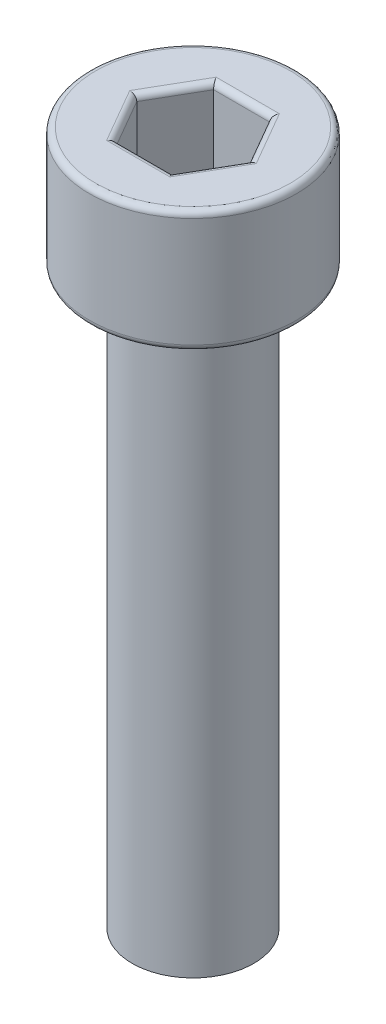
SolidWorks part; units mm, degrees
ref_plane "Front Plane" through (0, 0, 0) normal (0, 0, 1) x (1, 0, 0)
ref_plane "Top Plane" through (0, 0, 0) normal (0, 1, 0) x (1, 0, 0)
ref_plane "Right Plane" through (0, 0, 0) normal (1, 0, 0) x (0, 0, -1)
sketch "Sketch1" plane through (0, 0, 0) normal (0, 0, 1) x (1, 0, 0)
  line L0 (0, 21.3223) -> (0, -43.638) construction
sketch "Sketch2" plane through (0, 0, 0) normal (0, 0, 1) x (1, 0, 0)
  line L0 (0, 5) -> (4.25, 5)
  line L1 (0, 200021.3223) -> (0, -200043.638) construction
  line L2 (4.25, 5) -> (4.25, 0)
  line L3 (4.25, 0) -> (2.5, 0)
  line L4 (2.5, 0) -> (2.5, -23.5)
  line L5 (2.5, -23.5) -> (0, -23.5)
  line L6 (0, -23.5) -> (0, 5)
  dimension "D1" = 2.5
  dimension "D2" = 4.25
  dimension "D3" = 5
  dimension "D4" = 23.5
revolve "Revolve1" add sketch "Sketch2" angle 360 about L0
sketch "Sketch3" plane through (0, 5, 0) normal (0, 1, 0) x (1, 0, 0)
  line L0 (0, 0) -> (2.3094, 0) construction
  line L1 (2.3094, 0) -> (1.1547, 2)
  line L2 (1.1547, 2) -> (-1.1547, 2)
  line L3 (-1.1547, 2) -> (-2.3094, 0)
  line L4 (-2.3094, 0) -> (-1.1547, -2)
  line L5 (-1.1547, -2) -> (1.1547, -2)
  line L6 (1.1547, -2) -> (2.3094, 0)
  circle A0 centre (0, 0) radius 2 construction
  dimension "D1" = 4
extrude "Cut-Extrude1" cut sketch "Sketch3" against normal blind 3.5
fillet "Fillet1" radius 0.25 9 edges at (-2.5, 0, 0) (-4.25, 0, 0) (-4.25, 5, 0) (0, 5, -2) (-1.7321, 5, -1) (-1.7321, 5, 1) (0, 5, 2) (1.7321, 5, 1) (1.7321, 5, -1)
